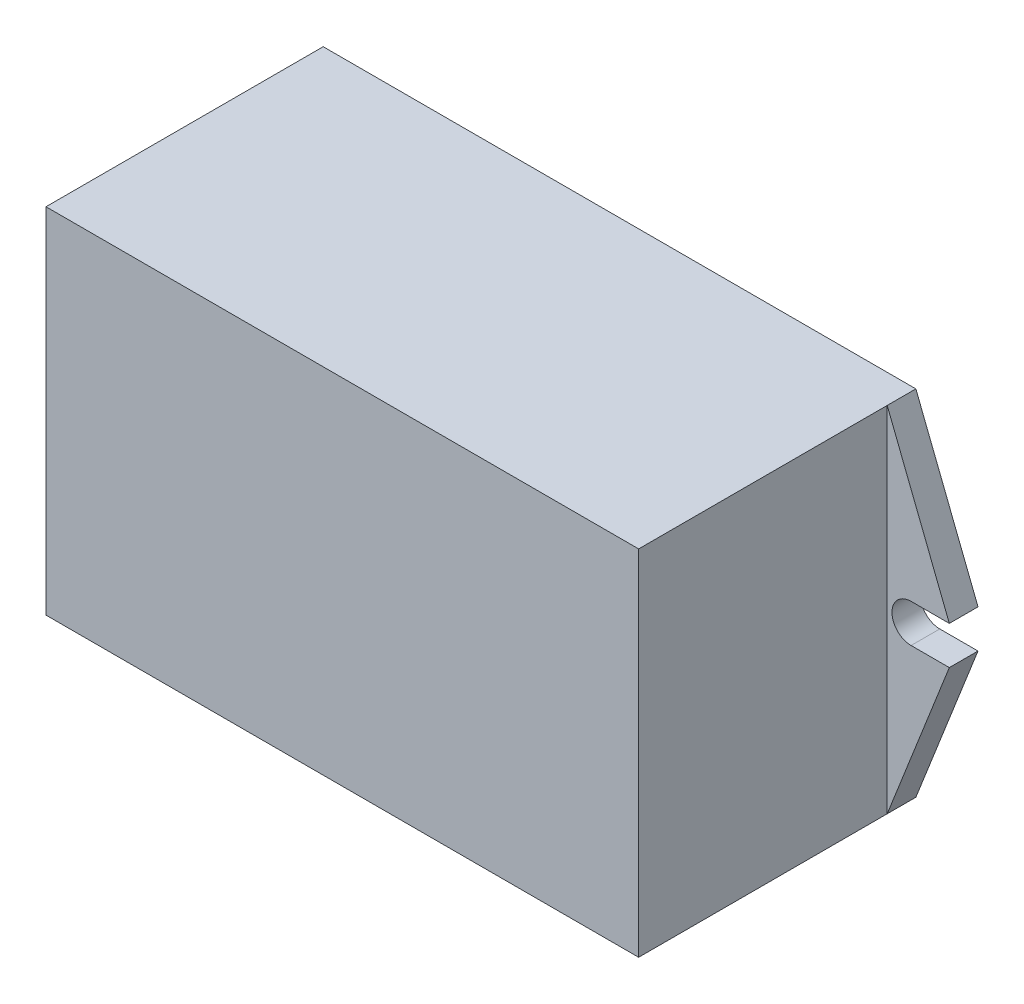
SolidWorks part; units mm, degrees
ref_plane "前视基准面" through (0, 0, 0) normal (0, 0, 1) x (1, 0, 0)
ref_plane "上视基准面" through (0, 0, 0) normal (0, 1, 0) x (1, 0, 0)
ref_plane "右视基准面" through (0, 0, 0) normal (1, 0, 0) x (0, 0, -1)
sketch "草图1" plane through (0, 0, 0) normal (0, 0, 1) x (1, 0, 0)
  line L0 (62, -18.5) -> (167.1989, -18.5)
  line L1 (0, 0) -> (62, 0)
  line L2 (0, 0) -> (0, -37) construction
  line L3 (0, -37) -> (62, -37)
  line L4 (62, 0) -> (62, -37) construction
  line L5 (64.5, -16.5) -> (68.5, -16.5)
  line L6 (64.5, -20.5) -> (68.5, -20.5)
  line L7 (68.5, -16.5) -> (62, 0)
  line L8 (68.5, -20.5) -> (62, -37)
  line L9 (31, 0) -> (31, -37) construction
  line L10 (0, 0) -> (0, -37) construction
  line L11 (-6.5, -20.5) -> (0, -37)
  line L12 (-6.5, -16.5) -> (0, 0)
  line L13 (-2.5, -20.5) -> (-6.5, -20.5)
  line L14 (-2.5, -16.5) -> (-6.5, -16.5)
  circle A0 centre (64.5, -18.5) radius 2 construction
  arc A1 (64.5, -20.5) -> (64.5, -16.5) centre (64.5, -18.5) cw
  circle A2 centre (-2.5, -18.5) radius 2 construction
  arc A3 (-2.5, -20.5) -> (-2.5, -16.5) centre (-2.5, -18.5) ccw
  dimension "D3" = 2.5
  dimension "D1" = 62
  dimension "D2" = 37
extrude "凸台-拉伸1" add sketch "草图1" along normal blind 3
sketch "草图2" plane through (0, 0, 3) normal (0, 0, 1) x (1, 0, 0)
  line L1 (0, 0) -> (62, 0)
  line L2 (0, 0) -> (0, -37)
  line L3 (0, -37) -> (62, -37)
  line L4 (62, 0) -> (62, -37)
extrude "凸台-拉伸2" add sketch "草图2" along normal blind 26
